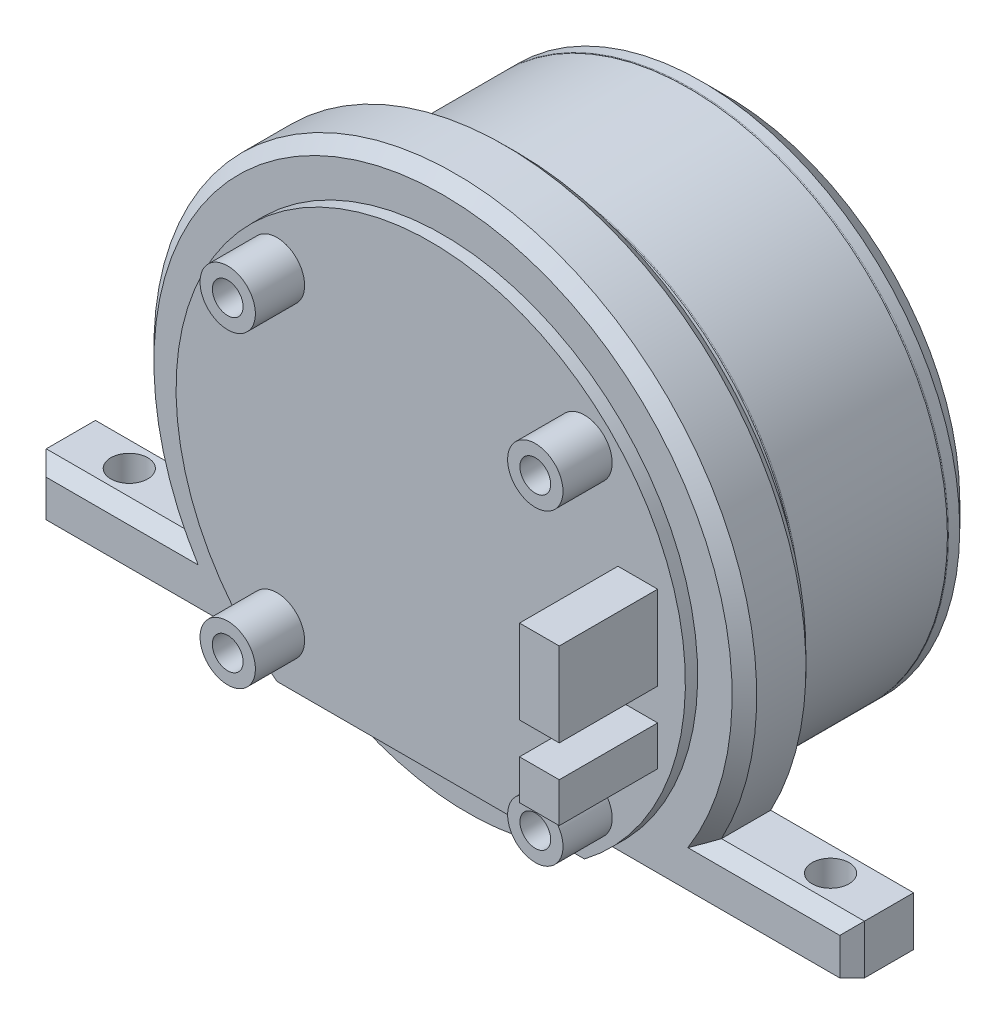
SolidWorks part; units mm, degrees
ref_plane "Front Plane" through (0, 0, 0) normal (0, 0, 1) x (1, 0, 0)
ref_plane "Top Plane" through (0, 0, 0) normal (0, 1, 0) x (1, 0, 0)
ref_plane "Right Plane" through (0, 0, 0) normal (1, 0, 0) x (0, 0, -1)
sketch "Sketch1" plane through (0, 0, 0) normal (0, 0, 1) x (1, 0, 0)
  circle A0 centre (0, 0) radius 21
  dimension "D1" = 42
extrude "Boss-Extrude1" add sketch "Sketch1" along normal blind 3
chamfer "Chamfer1" distance 2 angle 45 1 edges at (21, 0, 0)
fillet "Fillet1" radius 0.1 1 edges at (21, 0, 3)
sketch "Sketch2" plane through (0, 0, 3) normal (0, 0, 1) x (1, 0, 0)
  circle A0 centre (0, 0) radius 21 construction
  circle A1 centre (0, 0) radius 21
extrude "Boss-Extrude2" add sketch "Sketch2" along normal blind 12
fillet "Fillet2" radius 0.1 1 edges at (21, 0, 15)
sketch "Sketch3" plane through (0, 0, 15) normal (0, 0, 1) x (1, 0, 0)
  circle A0 centre (0, 0) radius 21 construction
  circle A1 centre (0, 0) radius 21
extrude "Boss-Extrude3" add sketch "Sketch3" along normal blind 6
sketch "Sketch4" plane through (0, 0, 0) normal (0, 0, -1) x (-1, 0, 0)
  line L0 (-10, 0) -> (0, 0) construction
  circle A0 centre (0, 0) radius 3
  circle A1 centre (-10, 0) radius 1.5
  circle A2 centre (0, 0) radius 3
  circle A3 centre (0, 10) radius 1.5
  circle A4 centre (0, 0) radius 3
  circle A5 centre (10, 0) radius 1.5
  circle A6 centre (0, 0) radius 3
  circle A7 centre (0, -10) radius 1.5
  point P17 (0, 0)
  dimension "D1" = 6
  dimension "D2" = 3
  dimension "D3" = 10
  dimension "D4" = 4
extrude "Cut-Extrude1" cut sketch "Sketch4" against normal blind 6
ref_plane "Plane1" through (0, 0, 17) normal (0, 0, 1) x (1, 0, 0)
sketch "Sketch5" plane through (0, 0, 17) normal (0, 0, 1) x (1, 0, 0)
  line L0 (21.6333, -11.5) -> (33.25, -11.5)
  line L1 (-33.25, -15.5) -> (33.25, -15.5)
  line L2 (-33.25, -15.5) -> (-33.25, -11.5)
  line L3 (-33.25, -11.5) -> (-21.6333, -11.5)
  line L4 (33.25, -15.5) -> (33.25, -11.5)
  line L5 (0, 0) -> (0, -15.5) construction
  arc A0 (21.6333, -11.5) -> (-21.6333, -11.5) centre (0, 0) ccw
  dimension "D1" = 49
  dimension "D2" = 66.5
  dimension "D3" = 4
  dimension "D4" = 15.5
extrude "Boss-Extrude4" add sketch "Sketch5" along normal blind 6
chamfer "Chamfer2" distance 1 angle 45 10 edges at (0, 24.5, 17) (0, 24.5, 23) (-33.25, -13.5, 17) (-27.4417, -11.5, 17) (33.25, -13.5, 17) (27.4417, -11.5, 17) (-33.25, -13.5, 23) (-27.4417, -11.5, 23) (33.25, -13.5, 23) (27.4417, -11.5, 23)
sketch "Sketch6" plane through (0, -11.5, 0) normal (0, 1, 0) x (1, 0, 0)
  line L0 (-28.5, -20) -> (28.5, -20) construction
  line L1 (0, -20) -> (0, 0) construction
  line L2 (19, 0) -> (-19, 0) construction
  line L3 (-23.5, -23) -> (23.5, -23) construction
  circle A0 centre (-28.5, -20) radius 1.5
  circle A1 centre (28.5, -20) radius 1.5
  dimension "D3" = 3
  dimension "D1" = 3
  dimension "D2" = 57
extrude "Cut-Extrude2" cut sketch "Sketch6" against normal through all and the other way through all
sketch "Sketch7" plane through (0, 0, 23) normal (0, 0, 1) x (1, 0, 0)
  line L0 (12.4996, -16.5) -> (-12.4996, -16.5)
  line L1 (-32.25, -15.5) -> (32.25, -15.5) construction
  arc A0 (12.4996, -16.5) -> (-12.4996, -16.5) centre (0, 0) ccw
  dimension "D2" = 20.7
  dimension "D1" = 1
extrude "Boss-Extrude5" add sketch "Sketch7" along normal blind 1
sketch "Sketch8" plane through (0, 0, 24) normal (0, 0, 1) x (1, 0, 0)
  line L1 (-12.5, 12.5) -> (12.5, 12.5) construction
  line L2 (-12.5, 12.5) -> (-12.5, -12.5) construction
  line L3 (-12.5, -12.5) -> (12.5, -12.5) construction
  line L4 (12.5, 12.5) -> (12.5, -12.5) construction
  line L5 (-12.5, 12.5) -> (12.5, -12.5) construction
  line L6 (-12.5, -12.5) -> (12.5, 12.5) construction
  circle A0 centre (-12.5, 12.5) radius 2.25
  circle A1 centre (12.5, 12.5) radius 2.25
  circle A2 centre (12.5, -12.5) radius 2.25
  circle A3 centre (-12.5, -12.5) radius 2.25
  point P0 (0, 0)
  dimension "D2" = 4.5
  dimension "D1" = 25
extrude "Boss-Extrude6" add sketch "Sketch8" along normal blind 4
sketch "Sketch9" plane through (0, 0, 28) normal (0, 0, 1) x (1, 0, 0)
  circle A2 centre (12.5, 12.5) radius 1.25
  circle A3 centre (12.5, 12.5) radius 1.25
  circle A4 centre (12.5, -12.5) radius 1.25
  circle A5 centre (12.5, -12.5) radius 1.25
  circle A8 centre (-12.5, 12.5) radius 1.25
  circle A9 centre (-12.5, 12.5) radius 1.25
  circle A11 centre (-12.5, -12.5) radius 1.25
  circle A12 centre (-12.5, -12.5) radius 1.25
  dimension "D1" = 1
  dimension "D2" = 1
  dimension "D3" = 1
  dimension "D4" = 1
extrude "Cut-Extrude3" cut sketch "Sketch9" against normal blind 4
sketch "Sketch10" plane through (0, 0, 24) normal (0, 0, 1) x (1, 0, 0)
  line L0 (15.2167, -1.355) -> (15.2167, -3.9466) construction
  line L1 (15.2167, 5.4678) -> (18.4459, 5.4678)
  line L2 (15.2167, 5.4678) -> (15.2167, -1.355)
  line L3 (15.2167, -1.355) -> (18.4459, -1.355)
  line L4 (18.4459, 5.4678) -> (18.4459, -1.355)
  line L5 (15.2167, -3.9466) -> (18.4459, -3.9466)
  line L6 (15.2167, -3.9466) -> (15.2167, -7.1758)
  line L7 (15.2167, -7.1758) -> (18.4459, -7.1758)
  line L8 (18.4459, -3.9466) -> (18.4459, -7.1758)
  line L9 (18.4459, -3.9466) -> (18.4459, -1.355) construction
extrude "Boss-Extrude7" add sketch "Sketch10" along normal blind 8
